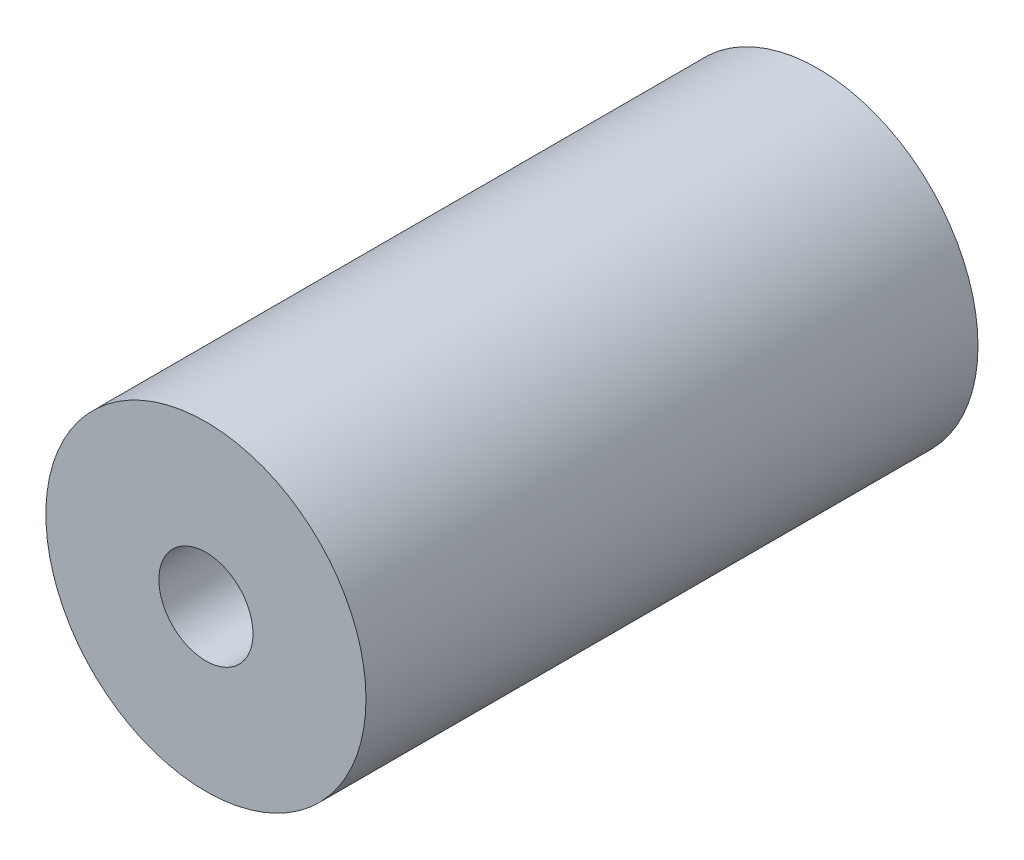
SolidWorks part; units mm, degrees
ref_plane "Front Plane" through (0, 0, 0) normal (0, 0, 1) x (1, 0, 0)
ref_plane "Top Plane" through (0, 0, 0) normal (0, 1, 0) x (1, 0, 0)
ref_plane "Right Plane" through (0, 0, 0) normal (1, 0, 0) x (0, 0, -1)
sketch "Sketch1" plane through (0, 0, 0) normal (0, 0, 1) x (1, 0, 0)
  circle A0 centre (0, 0) radius 17
  dimension "D1" = 34
extrude "Boss-Extrude1" add sketch "Sketch1" along normal blind 65
sketch "Sketch2" plane through (0, 0, 65) normal (0, 0, 1) x (1, 0, 0)
  circle A0 centre (0, 0) radius 5
  dimension "D1" = 10
extrude "Cut-Extrude1" cut sketch "Sketch2" against normal blind 150 contours A0
